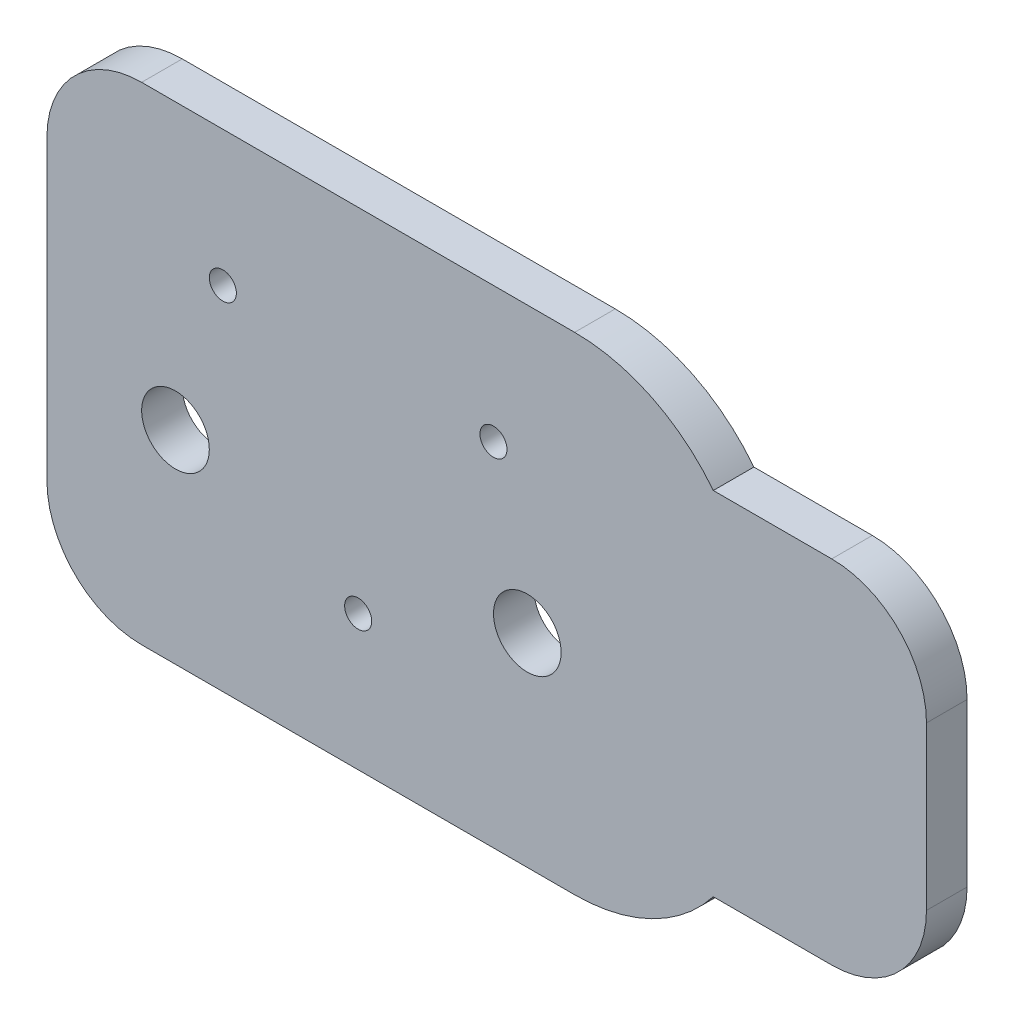
SolidWorks part; units mm, degrees
ref_plane "Front Plane" through (0, 0, 0) normal (0, 0, 1) x (1, 0, 0)
ref_plane "Top Plane" through (0, 0, 0) normal (0, 1, 0) x (1, 0, 0)
ref_plane "Right Plane" through (0, 0, 0) normal (1, 0, 0) x (0, 0, -1)
sketch "Sketch1" plane through (0, 0, 0) normal (0, 0, 1) x (1, 0, 0)
  line L0 (-18, 11) -> (-18, -11)
  line L1 (-16, -13) -> (16, -13)
  line L2 (-16, 13) -> (16, 13)
  line L3 (24.6603, 8) -> (35, 8)
  line L4 (55, 0) -> (-55, 0) construction
  line L5 (24.6603, -8) -> (35, -8)
  line L6 (37, 6) -> (37, -6)
  arc A0 (16, 13) -> (22.9282, 9) centre (16, 5) cw
  arc A1 (22.9282, 9) -> (24.6603, 8) centre (24.6603, 10) ccw
  arc A2 (22.9282, -9) -> (24.6603, -8) centre (24.6603, -10) cw
  arc A3 (16, -13) -> (22.9282, -9) centre (16, -5) ccw
  arc A4 (35, -8) -> (37, -6) centre (35, -6) ccw
  arc A5 (35, 8) -> (37, 6) centre (35, 6) cw
  arc A6 (-18, -11) -> (-16, -13) centre (-16, -11) ccw
  arc A7 (-18, 11) -> (-16, 13) centre (-16, 11) cw
  point P5 (-18, 0)
  point P7 (0, 13)
  point P21 (37, -8)
  point P24 (37, 8)
  point P27 (-18, -13)
  point P30 (-18, 13)
  point P31 (37, 0)
  dimension "D3" = 2
  dimension "D4" = 2
  dimension "D7" = 8
  dimension "D8" = 2
  dimension "D1" = 26
  dimension "D2" = 34
  dimension "D5" = 16
  dimension "D6" = 55
extrude "Insert in sheet metal hole" add sketch "Sketch1" along normal blind 1
sketch "Sketch2" plane through (0, 0, 1) normal (0, 0, 1) x (1, 0, 0)
  line L12 (26.247, -13) -> (35, -13)
  line L13 (42, -6) -> (42, 6)
  line L14 (35, 13) -> (26.247, 13)
  line L15 (16, 18) -> (-16, 18)
  line L16 (-23, 11) -> (-23, -11)
  line L17 (-16, -18) -> (16, -18)
  line L18 (26.247, -13) -> (35, -13)
  line L19 (42, -6) -> (42, 6)
  line L20 (35, 13) -> (26.247, 13)
  line L21 (16, 18) -> (-16, 18)
  line L22 (-23, 11) -> (-23, -11)
  line L23 (-16, -18) -> (16, -18)
  arc A16 (16, -18) -> (26.247, -13) centre (16, -5) ccw
  arc A17 (35, -13) -> (42, -6) centre (35, -6) ccw
  arc A18 (42, 6) -> (35, 13) centre (35, 6) ccw
  arc A19 (26.247, 13) -> (16, 18) centre (16, 5) ccw
  arc A20 (-16, 18) -> (-23, 11) centre (-16, 11) ccw
  arc A21 (-23, -11) -> (-16, -18) centre (-16, -11) ccw
  arc A22 (16, -18) -> (26.247, -13) centre (16, -5) ccw
  arc A23 (35, -13) -> (42, -6) centre (35, -6) ccw
  arc A24 (42, 6) -> (35, 13) centre (35, 6) ccw
  arc A25 (26.247, 13) -> (16, 18) centre (16, 5) ccw
  arc A26 (-16, 18) -> (-23, 11) centre (-16, 11) ccw
  arc A27 (-23, -11) -> (-16, -18) centre (-16, -11) ccw
  dimension "D1" = 5
extrude "Backing" add sketch "Sketch2" against normal blind 3
sketch "Sketch3" plane through (0, 0, 1) normal (0, 0, 1) x (1, 0, 0)
  circle A0 centre (-10, 8) radius 1
  circle A1 centre (10, 8) radius 1
  circle A2 centre (0, -8) radius 1
  dimension "D1" = 2
  dimension "D2" = 8
  dimension "D3" = 10
  dimension "D4" = 10
  dimension "D5" = 8
extrude "Screwholes" cut sketch "Sketch3" against normal through all both and the other way through all
sketch "Sketch4" plane through (0, 0, 1) normal (0, 0, 1) x (1, 0, 0)
  circle A0 centre (-13.5, -3) radius 2.5
  circle A1 centre (12.5, -3) radius 2.5
  circle A2 centre (0, -8) radius 1 construction
  dimension "D3" = 5
  dimension "D4" = 5
  dimension "D1" = 13.5
  dimension "D2" = 12.5
extrude "Wire holes" cut sketch "Sketch4" against normal through all both and the other way through all
